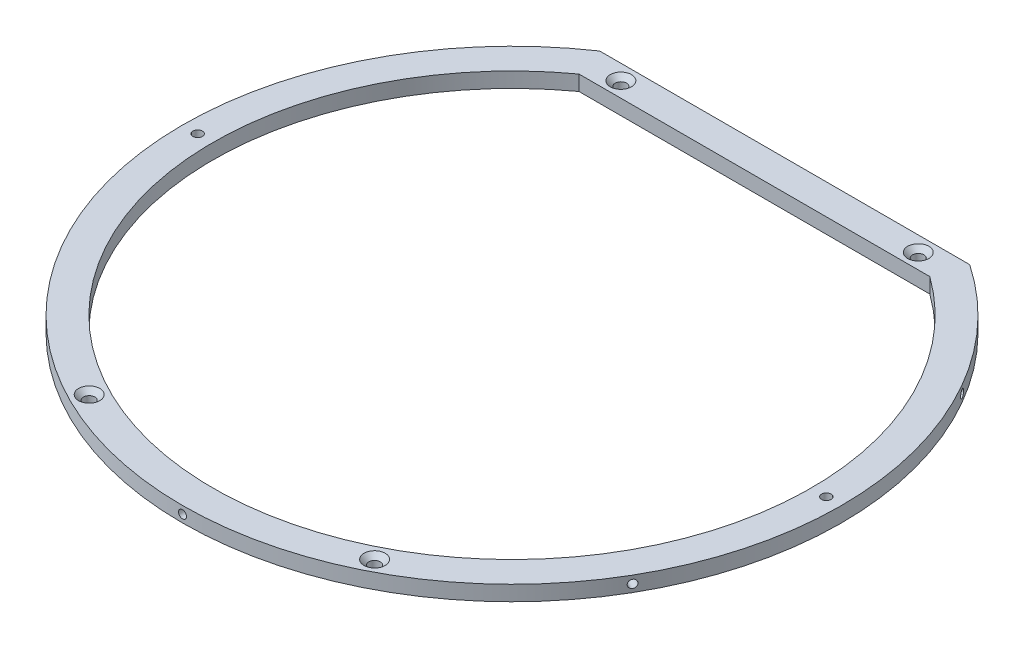
SolidWorks part; units mm, degrees
material "6061 Alloy"
ref_plane "Front Plane" through (0, 0, 0) normal (0, 0, 1) x (1, 0, 0)
ref_plane "Top Plane" through (0, 0, 0) normal (0, 1, 0) x (1, 0, 0)
ref_plane "Right Plane" through (0, 0, 0) normal (1, 0, 0) x (0, 0, -1)
sketch "Sketch1" plane through (0, 0, 0) normal (0, 1, 0) x (1, 0, 0)
  line L0 (0, 0) -> (0, 72) construction
  line L1 (-48.8365, 72) -> (48.8365, 72)
  line L2 (-46.3141, 64) -> (46.3141, 64)
  arc A0 (-48.8365, 72) -> (48.8365, 72) centre (0, 0) ccw
  arc A1 (-46.3141, 64) -> (46.3141, 64) centre (0, 0) ccw
  point P7 (0, 0)
  dimension "D1" = 8
extrude "Boss-Extrude1" add sketch "Sketch1" along normal mid plane 4
sketch "Sketch2" plane through (0, 2, 0) normal (0, 1, 0) x (1, 0, 0)
  line L0 (0, 0) -> (-37.6812, -73.9535) construction
  line L1 (0, 0) -> (37.6812, -73.9535) construction
  line L2 (0, 0) -> (-39.2598, 68) construction
  line L3 (0, 0) -> (39.2598, 68) construction
  line L4 (-39.2598, 68) -> (39.2598, 68) construction
  line L5 (48.8365, 72) -> (-48.8365, 72) construction
  line L6 (0, 0) -> (71.8801, 41.5) construction
  line L7 (0, 0) -> (-71.8801, -41.5) construction
  line L8 (0, 0) -> (-71.8801, 41.5) construction
  line L9 (0, 0) -> (71.8801, -41.5) construction
  line L10 (0, 0) -> (0, 72) construction
  line L23 (-83, 0) -> (83, 0) construction
  point P26 (0, 0)
  dimension "D1" = 4
  dimension "D2" = 27
  dimension "D3" = 83
  dimension "D5" = 166
hole_wizard "CSK for M3 SFHCS1" positions "3DSketch2" profile "Sketch4" countersink size "M3" standard "ANSI Metric"
sketch3d "3DSketch2"
  point P12 (-37.6812, 2, 73.9535)
  point P30 (-39.2598, 2, -68)
  point P33 (39.2598, 2, -68)
  point P36 (37.6812, 2, 73.9535)
sketch "Sketch4" plane through (-37.6812, 2, 73.9535) normal (1, 0, 0) x (0, 0, 1)
  line L0 (0, 0) -> (0, 10.4013)
  line L1 (0, 10.4013) -> (1.5, 9.5)
  line L2 (1.5, 9.5) -> (1.5, 1.3)
  line L3 (1.5, 1.3) -> (2.8, 0)
  line L5 (2.8, 0) -> (0, 0)
  line L6 (-1.5, 1.3) -> (-2.8, 0) construction
  line L10 (0, 10.4013) -> (-1.5, 9.5) construction
  line L11 (0, -6.35) -> (0, 107.95) construction
  dimension "Hole Dia." = 3
  dimension "Hole Depth" = 9.5
  dimension "Near C'Sink Dia." = 5.6
  dimension "Near C'Sink Angle" = 90
  dimension "Drill Angle" = 118
sketch "Sketch5" plane through (0, 0, 0) normal (0, 1, 0) x (1, 0, 0)
  line L0 (0, 0) -> (-75.3442, 43.5) construction
  line L1 (0, 0) -> (-75.3442, -43.5) construction
  line L2 (0, 0) -> (0, 72) construction
  line L3 (48.8365, 72) -> (-48.8365, 72) construction
  line L4 (0, 0) -> (75.3442, -43.5) construction
  line L5 (0, 0) -> (75.3442, 43.5) construction
  arc A0 (-48.8365, 72) -> (48.8365, 72) centre (0, 0) ccw construction
  dimension "D1" = 60
  dimension "D2" = 60
ref_plane "Plane1" through (75.3442, 0, -43.5) normal (0.866, 0, -0.5) x (-0.5, 0, -0.866)
sketch "Sketch6" plane through (75.3442, 0, -43.5) normal (0.866, 0, -0.5) x (-0.5, 0, -0.866)
  circle A0 centre (0, 0) radius 1.05
  dimension "D1" = 2.1
extrude "Cut-Extrude1" cut sketch "Sketch6" against normal blind 6
ref_plane "Plane2" through (75.3442, 0, 43.5) normal (0.866, 0, 0.5) x (0.5, 0, -0.866)
sketch "Sketch7" plane through (75.3442, 0, 43.5) normal (0.866, 0, 0.5) x (0.5, 0, -0.866)
  circle A0 centre (0, 0) radius 1.05
  dimension "D1" = 2.1
extrude "Cut-Extrude2" cut sketch "Sketch7" against normal blind 6
mirror "Mirror1" about plane through (0, 0, 0) normal (1, 0, 0) of "Cut-Extrude2", "Cut-Extrude1"
ref_plane "Plane3" through (0, 0, 87) normal (0, 0, 1) x (1, 0, 0)
sketch "Sketch8" plane through (0, 0, 87) normal (0, 0, 1) x (1, 0, 0)
  circle A0 centre (0, 0) radius 1.05
  dimension "D1" = 2.1
extrude "Cut-Extrude3" cut sketch "Sketch8" against normal blind 6
hole_wizard "M2.5x0.45 Tapped Hole1" positions "3DSketch3" profile "Sketch9" tap size "M2.5x0.45" standard "ANSI Metric"
sketch3d "3DSketch3"
  line L0 (48.8365, -2, -72) -> (-48.8365, -2, -72) construction
  line L1 (48.8365, 2, -72) -> (48.8365, -2, -72) construction
  line L2 (-48.8365, 2, -72) -> (-48.8365, -2, -72) construction
  point P0 (33.8365, 0, -72)
  point P2 (-33.8365, 0, -72)
  dimension "D1" = 2
  dimension "D2" = 15
  dimension "D3" = 15
sketch "Sketch9" plane through (33.8365, 0, -72) normal (1, 0, 0) x (0, 1, 0)
  line L0 (0, 0) -> (0, 6.9659)
  line L1 (0, 6.9659) -> (1.025, 6.35)
  line L2 (1.025, 6.35) -> (1.025, 0)
  line L5 (1.025, 0) -> (0, 0)
  line L10 (0, 6.9659) -> (-1.025, 6.35) construction
  line L11 (0, -6.35) -> (0, 107.95) construction
  dimension "Tap Drill Dia." = 2.05
  dimension "Tap Drill Depth" = 6.35
  dimension "Drill Angle" = 118
hole_wizard "Tap Drill for M3x0.5 Tap1" positions "3DSketch4" profile "Sketch10" hole size "M3x0.5" standard "ANSI Metric" end condition through all
sketch3d "3DSketch4"
  point P0 (-83, 2, 0)
  point P3 (83, 2, 0)
sketch "Sketch10" plane through (-83, 2, 0) normal (1, 0, 0) x (0, 0, 1)
  line L0 (0, 0) -> (0, 4)
  line L1 (0, 4) -> (1.25, 4)
  line L2 (1.25, 4) -> (1.25, 0)
  line L5 (1.25, 0) -> (0, 0)
  line L11 (0, -6.35) -> (0, 107.95) construction
  dimension "Thru Hole Dia." = 2.5
  dimension "Thru Hole Depth" = 4
sketch "Sketch11" plane through (0, 2, 0) normal (0, 1, 0) x (1, 0, 0)
  point P0 (0, 0)
